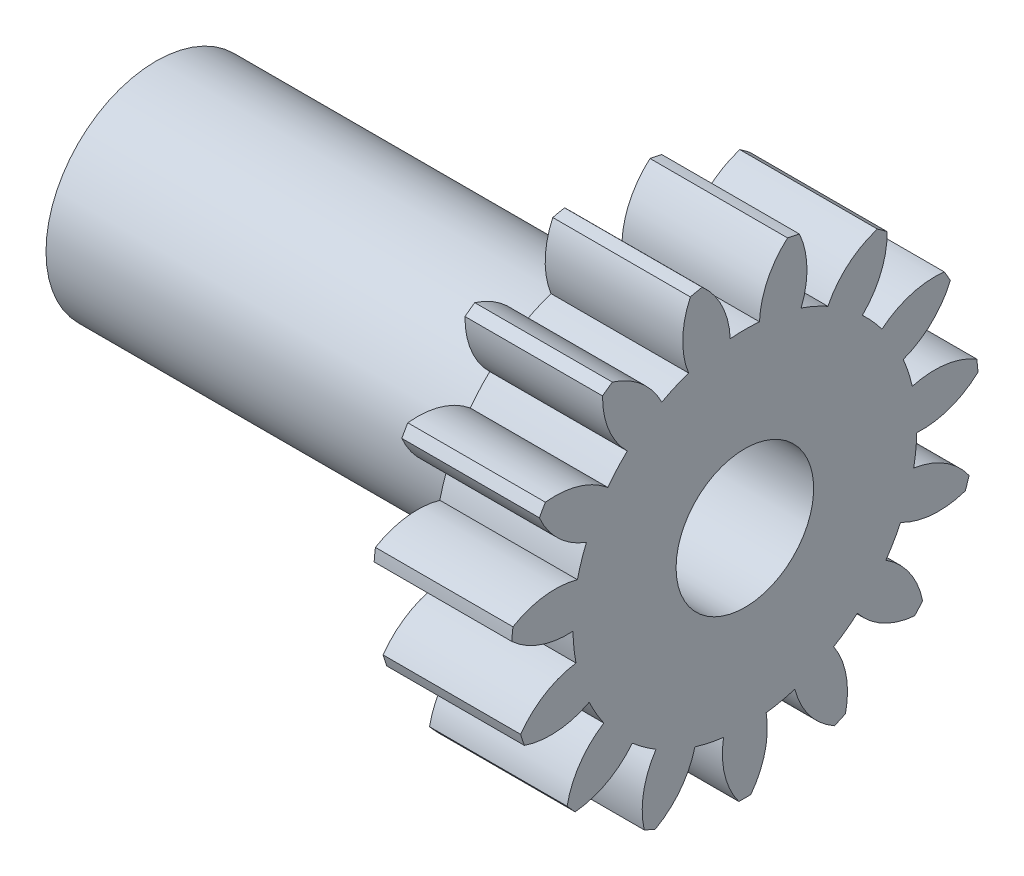
SolidWorks part; units mm, degrees
ref_plane "Plane1" through (0, 0, 0) normal (0, 0, 1) x (1, 0, 0)
ref_plane "Plane2" through (0, 0, 0) normal (0, 1, 0) x (1, 0, 0)
ref_plane "Plane3" through (0, 0, 0) normal (1, 0, 0) x (0, 0, -1)
sketch "HoldingSke" plane through (0, 0, 0) normal (0, 1, 0) x (1, 0, 0)
  line L0 (0, 0) -> (0.9659, -0.2588)
  line L1 (-15, 0) -> (100, 0) construction
  line L2 (0, 0) -> (-2.1039, 2.3779)
  line L3 (0, 0) -> (-11.863, 4.5341)
  line L4 (0, 0) -> (8.3417, 2.2352)
  line L5 (0, 0) -> (-20.0508, -7.4784)
  line L6 (0, 0) -> (-4.1448, -2.7965)
  line L7 (-2.1039, 2.3779) -> (2.5025, 23.2763)
  line L8 (-76.2, 54.61) -> (-75.3, 54.61)
  line L9 (-71.009, 38.7566) -> (-53.1078, 45.2721)
  line L10 (-76.2, 71.12) -> (104.1128, 71.12)
  line L11 (0, 0) -> (-5, 0)
  line L12 (-76.2, 101.6) -> (-76.162, 101.6)
  line L13 (24.9733, 27.94) -> (52.9518, 28.4284)
  line L14 (24.9733, 27.94) -> (24.9743, 27.94)
  line L15 (24.9733, 27.94) -> (100.4006, 29.5858)
  line L16 (-63.627, -1) -> (-12.827, -1)
  circle A0 centre (0, 0) radius 2.5
  circle A1 centre (0, 0) radius 4
  circle A2 centre (0, 0) radius 4
  circle A3 centre (0, 0) radius 2.5
  dimension "MHD" = 8
  dimension "Hub_dia" = 8
  dimension "Bore" = 5
  dimension "MBD" = 5
  dimension "Num_teeth" = 15
  dimension "Pitch" = 1
  dimension "Overall_len" = 21.4
  dimension "Show_teeth" = 15
  dimension "Thickness" = 5
  dimension "OAL" = 21.4001
  dimension "T_dim" = 0.9
  dimension "Ap" = 20
  dimension "H" = 19.05
  dimension "Pitch_radius" = 180.3128
  dimension "Width" = 5
  dimension "Backlash" = 0.038
  dimension "Addendum_fac" = 1
  dimension "Dedendum_fac" = 1.25
  dimension "Clearance_fac" = 0.25
  dimension "Dedendum_add" = 0.001
  dimension "Module" = 1
sketch "BasProSke" plane through (0, 0, 0) normal (0, 1, 0) x (1, 0, 0)
  line L0 (-10, 0) -> (60, 0) construction
  line L1 (0, 0) -> (0, 8.5)
  line L2 (0, 0) -> (5, 0)
  line L3 (5, 0) -> (5, 8.5)
  line L4 (5, 8.5) -> (0, 8.5)
  dimension "Thickness" = 5
  dimension "Diameter" = 17
revolve "Base-Revolve" add sketch "BasProSke" angle 360 about L0
sketch "TooCutSke" plane through (0, 0, 0) normal (1, 0, 0) x (0, 0, -1)
  line L1 (0, 0) -> (0, 107) construction
  line L2 (0, 0) -> (-0.8504, 7.4516) construction
  line L3 (0, 0) -> (-3.1044, 14.6049) construction
  line L4 (-0.8504, 7.4516) -> (-1.5522, 7.3025) construction
  arc A0 (0.5316, 6.2263) -> (-0.5316, 6.2263) centre (0, 0) ccw
  arc A1 (1.5766, 8.3784) -> (-1.5766, 8.3784) centre (0, 0) ccw
  circle A2 centre (0, 0) radius 7.5 construction
  circle A3 centre (0, 0) radius 7.0477 construction
  arc A4 (-0.5316, 6.2263) -> (-1.5766, 8.3784) centre (-3.5289, 6.1005) ccw
  arc A5 (1.5766, 8.3784) -> (0.5316, 6.2263) centre (3.5289, 6.1005) ccw
  dimension "Root_dia" = 12.498
  dimension "Overcut_dia" = 17.0508
  dimension "Pitch_dia" = 15
  dimension "Base_dia" = 14.0954
  dimension "Flank_rad" = 3
  dimension "Half_ang" = 12
  dimension "Half_CT" = 0.7175
extrude "ToothCut" cut sketch "TooCutSke" along normal through all
fillet "Breaks" [suppressed] radius 0.02
fillet "RootFillets" [suppressed] radius 0.251
pattern_circular "TeethCuts" count 15 every 24 about axis through (-10, 0, 0) along (1, 0, 0) of "ToothCut", "RootFillets", "Breaks"
sketch "HubNeaOneSke" plane through (0, 0, 0) normal (-1, 0, 0) x (0, 0, 1)
  circle A0 centre (0, 0) radius 4
  dimension "Diameter" = 8
extrude "HubNearOne" add sketch "HubNeaOneSke" along normal blind 16.4001
sketch "HubNeaBotSke" plane through (0, 0, 0) normal (-1, 0, 0) x (0, 0, 1)
  circle A0 centre (0, 0) radius 4
  dimension "Diameter" = 8
extrude "HubNearBoth" [suppressed] add sketch "HubNeaBotSke" along normal blind 8.2
ref_plane "FarPln" through (5, 0, 0) normal (1, 0, 0) x (0, 0, -1)
sketch "HubFarSke" plane through (5, 0, 0) normal (1, 0, 0) x (0, 0, -1)
  circle A0 centre (0, 0) radius 4
  dimension "Diameter" = 8
extrude "HubFar" [suppressed] add sketch "HubFarSke" along normal blind 8.2
sketch "BorSke" plane through (0, 0, 0) normal (1, 0, 0) x (0, 0, -1)
  circle A0 centre (0, 0) radius 2.5
  dimension "Diameter" = 5
extrude "Bore" cut sketch "BorSke" along normal mid plane 42.8001
sketch "KeySke" plane through (0, 0, 0) normal (1, 0, 0) x (0, 0, -1)
  line L0 (-1, 0) -> (-1, 3.4)
  line L1 (-1, 3.4) -> (1, 3.4)
  line L2 (1, 3.4) -> (1, 0)
  line L3 (0, 0) -> (0, 34) construction
  line L4 (-1, 0) -> (1, 0)
  dimension "Offset" = 3.4
  dimension "Width" = 2
extrude "Keyway" [suppressed] cut sketch "KeySke" along normal mid plane 42.8001
pattern_circular "Keyway2" [suppressed] count 2 every 90 about axis through (-10, 0, 0) along (1, 0, 0)
sketch "草图1" plane through (5, 0, 0) normal (1, 0, 0) x (0, 0, -1)
  circle A0 centre (0, 0) radius 7.5
  dimension "D1" = 15
equation "' \"Module@HoldingSke\" = 6.35"
equation "' \"Num_teeth@HoldingSke\" = 12"
equation "' \"Ap@HoldingSke\" =  20"
equation "' \"Ap@HoldingSke\" = 20"
equation "' \"Width@HoldingSke\" = 0.5 * 25.4"
equation "' \"Hub_dia@HoldingSke\"= 1 * 25.4"
equation "' \"Hub_dia@HoldingSke\" = 1 * 25.4"
equation "' \"Overall_len@HoldingSke\" = 1.0 * 25.4"
equation "' \"Bore@HoldingSke\" = 0.75 * 25.4"
equation "' \"T_dim@HoldingSke\" = 0.1 * 25.4"
equation "' \"Width@KeySke\" = 0.25 * 25.4"
equation "' \"Show_teeth@HoldingSke\" = 13"
equation "' \"Backlash@HoldingSke\" = 0.009 * 25.4"
equation "' \"Addendum_fac@HoldingSke\" = 1.0"
equation "' \"Dedendum_fac@HoldingSke\" = 1.25"
equation "' \"Dedendum_add@HoldingSke\" = 0.00005 * 25.4"
equation "' \"Clearance_fac@HoldingSke\" = 0.25"
equation "\"Pitch@HoldingSke\" = 1 / \"Module@HoldingSke\""
equation "\"Overcut_dia@TooCutSke\" = (\"Num_teeth@HoldingSke\" + 2 * \"Addendum_fac@HoldingSke\") / \"Pitch@HoldingSke\" + 0.002 * 25.4"
equation "\"Pitch_dia@TooCutSke\" = \"Num_teeth@HoldingSke\" / \"Pitch@HoldingSke\""
equation "\"Base_dia@TooCutSke\" = \"Num_teeth@HoldingSke\" / \"Pitch@HoldingSke\" * cos((\"Ap@HoldingSke\"  * 3.14159265 / 180))"
equation "\"Root_dia@TooCutSke\" = (\"Num_teeth@HoldingSke\" + 2) / \"Pitch@HoldingSke\" - 2 * (\"Addendum_fac@HoldingSke\" + \"Dedendum_fac@HoldingSke\") / \"Pitch@HoldingSke\" - \"Dedendum_add@HoldingSke\" * 2"
equation "\"Half_ang@TooCutSke\" = 180 / \"Num_teeth@HoldingSke\""
equation "\"Half_CT@TooCutSke\" = \"Num_teeth@HoldingSke\" / \"Pitch@HoldingSke\" * sin((3.14159265 / 2 / \"Num_teeth@HoldingSke\")) / 2 - 7 * \"Backlash@HoldingSke\" / 4"
equation "\"Flank_rad@TooCutSke\" = \"Num_teeth@HoldingSke\" / \"Pitch@HoldingSke\" / 5"
equation "\"Radius@RootFillets\" = \"Clearance_fac@HoldingSke\" / \"Pitch@HoldingSke\" + \"Dedendum_add@HoldingSke\""
equation "\"Break_rad@Breaks\" = 0.02 / \"Pitch@HoldingSke\""
equation "\"Thickness@HoldingSke\" = \"Width@HoldingSke\""
equation "\"OAL@HoldingSke\" = \"Thickness@HoldingSke\""
equation "\"MHD@HoldingSke\" = (\"Num_teeth@HoldingSke\" + 2) / \"Pitch@HoldingSke\" - 2 * (\"Addendum_fac@HoldingSke\" + \"Dedendum_fac@HoldingSke\")  / \"Pitch@HoldingSke\" - \"Dedendum_add@HoldingSke\" * 2"
equation "\"MBD@HoldingSke\" = (\"Num_teeth@HoldingSke\" + 2) / \"Pitch@HoldingSke\" - 2 * (\"Addendum_fac@HoldingSke\" + \"Dedendum_fac@HoldingSke\")  / \"Pitch@HoldingSke\" - \"Dedendum_add@HoldingSke\" * 2 - 0.002 * 25.4"
equation "\"MHD@HoldingSke\" = ((sgn( \"MHD@HoldingSke\" - \"Hub_dia@HoldingSke\" )-1)*( \"MHD@HoldingSke\" - \"Hub_dia@HoldingSke\" ))/-2+ \"Hub_dia@HoldingSke\""
equation "\"MBD@HoldingSke\" = ((sgn( \"MBD@HoldingSke\" - \"Bore@HoldingSke\" )-1)*( \"MBD@HoldingSke\" - \"Bore@HoldingSke\" ))/-2+ \"Bore@HoldingSke\""
equation "\"OAL@HoldingSke\" = ((sgn( \"OAL@HoldingSke\" - \"Overall_len@HoldingSke\" )+1)*( \"OAL@HoldingSke\" - \"Overall_len@HoldingSke\" ))/2 + \"Overall_len@HoldingSke\" + 0.000002 * 25.4"
equation "\"Num_teeth@TeethCuts\" = int( \"Show_teeth@HoldingSke\" ) + 1"
equation "\"Num_teeth@TeethCuts\" = ((sgn( \"Num_teeth@TeethCuts\" - \"Num_teeth@HoldingSke\" )-1)*( \"Num_teeth@TeethCuts\" - \"Num_teeth@HoldingSke\" ))/-2+ \"Num_teeth@HoldingSke\""
equation "\"Num_teeth@TeethCuts\" = ((sgn( \"Num_teeth@TeethCuts\" - 2.0)+1)*( \"Num_teeth@TeethCuts\" - 2.0))/2 +2.0"
equation "\"Angle@TeethCuts\" = 360.0 / \"Num_teeth@HoldingSke\""
equation "\"Diameter@BasProSke\" = (\"Num_teeth@HoldingSke\" + 2 * \"Addendum_fac@HoldingSke\") / \"Pitch@HoldingSke\""
equation "\"Thickness@BasProSke\"  = \"Thickness@HoldingSke\""
equation "' \"Fillet_rad@BasProSke\" =  \"Thickness@HoldingSke\" * 0.05"
equation "' \"Fillet_rad@BasProSke\" = \"Thickness@HoldingSke\" * 0.05"
equation "\"MHD@HoldingSke\" = ((sgn( \"MHD@HoldingSke\" - \"Root_dia@TooCutSke\" )-1)*( \"MHD@HoldingSke\" - \"Root_dia@TooCutSke\" ))/-2+ \"Root_dia@TooCutSke\""
equation "\"Diameter@HubNeaOneSke\" = \"MHD@HoldingSke\""
equation "\"Length@HubNearOne\" = \"OAL@HoldingSke\" - \"Thickness@BasProSke\""
equation "\"Diameter@HubNeaBotSke\" = \"MHD@HoldingSke\""
equation "\"Length@HubNearBoth\" = ( \"OAL@HoldingSke\" - \"Thickness@BasProSke\" ) / 2.0"
equation "\"Thickness@FarPln\" = \"Thickness@BasProSke\""
equation "\"Diameter@HubFarSke\" = \"MHD@HoldingSke\""
equation "\"Length@HubFar\" = ( \"OAL@HoldingSke\" - \"Thickness@BasProSke\" ) / 2.0"
equation "\"Diameter@BorSke\" = \"MBD@HoldingSke\""
equation "\"D1@Bore\" = \"OAL@HoldingSke\" * 2.0"
equation "\"D1@Keyway\" = \"OAL@HoldingSke\" * 2.0"
equation "\"Offset@KeySke\" = \"T_dim@HoldingSke\" + \"MBD@HoldingSke\" / 2.0"
